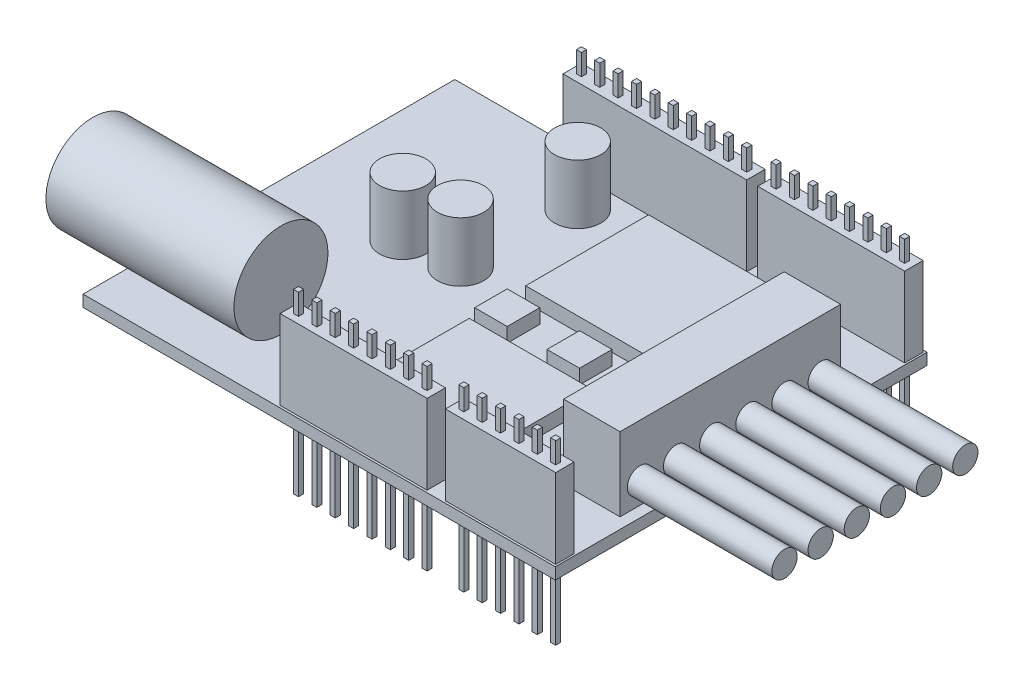
SolidWorks part; units mm, degrees
ref_plane "Plan de face" through (0, 0, 0) normal (0, 0, 1) x (1, 0, 0)
ref_plane "Plan de dessus" through (0, 0, 0) normal (0, 1, 0) x (1, 0, 0)
ref_plane "Plan de droite" through (0, 0, 0) normal (1, 0, 0) x (0, 0, -1)
sketch "Esquisse1" plane through (0, 0, 0) normal (0, 1, 0) x (1, 0, 0)
  line L1 (-32.65, 25.7) -> (32.65, 25.7)
  line L2 (-32.65, 25.7) -> (-32.65, -25.7)
  line L3 (-32.65, -25.7) -> (32.65, -25.7)
  line L4 (32.65, 25.7) -> (32.65, -25.7)
  point P4 (0, 25.7)
  point P6 (-32.65, 0)
  dimension "D1" = 65.3
  dimension "D2" = 51.4
extrude "Boss.-Extru.1" add sketch "Esquisse1" along normal blind 1.6
sketch "Esquisse2" plane through (0, 1.6, 0) normal (0, 1, 0) x (1, 0, 0)
  line L0 (0, 0) -> (8.1488, 0) construction
  line L1 (-1.05, 20.9) -> (15.95, 20.9)
  line L2 (-1.05, 20.9) -> (-1.05, 3.9)
  line L3 (-1.05, 3.9) -> (15.95, 3.9)
  line L4 (15.95, 20.9) -> (15.95, 3.9)
  line L5 (-1.05, -3.9) -> (15.95, -3.9)
  line L6 (15.95, -20.9) -> (15.95, -3.9)
  line L7 (-1.05, -20.9) -> (15.95, -20.9)
  line L8 (-1.05, -20.9) -> (-1.05, -3.9)
  line L9 (-32.65, 25.7) -> (-32.65, -25.7) construction
  line L10 (-1.95, 2.25) -> (2.55, 2.25)
  line L11 (-1.95, 2.25) -> (-1.95, -2.25)
  line L12 (-1.95, -2.25) -> (2.55, -2.25)
  line L13 (2.55, 2.25) -> (2.55, -2.25)
  line L14 (8.05, 2.25) -> (12.55, 2.25)
  line L15 (8.05, 2.25) -> (8.05, -2.25)
  line L16 (8.05, -2.25) -> (12.55, -2.25)
  line L17 (12.55, 2.25) -> (12.55, -2.25)
  point P15 (2.55, 0)
  dimension "D1" = 17
  dimension "D2" = 4.5
  dimension "D3" = 7.8
  dimension "D4" = 31.6
  dimension "D5" = 5.5
  dimension "D6" = 30.7
extrude "Boss.-Extru.2" add sketch "Esquisse2" along normal blind 2 separate body
sketch "Esquisse3" plane through (0, 1.6, 0) normal (0, 1, 0) x (1, 0, 0)
  line L0 (-32.65, 25.7) -> (-32.65, -25.7) construction
  line L1 (32.65, 25.7) -> (-32.65, 25.7) construction
  circle A0 centre (-8.55, 18.6) radius 3.2
  circle A1 centre (-9.75, 3.6) radius 3.2
  circle A2 centre (-16.95, 2.8) radius 3.2
  dimension "D1" = 6.4
  dimension "D2" = 15.7
  dimension "D3" = 22.9
  dimension "D4" = 24.1
  dimension "D5" = 7.1
  dimension "D6" = 22.1
  dimension "D7" = 22.9
extrude "Boss.-Extru.3" add sketch "Esquisse3" along normal blind 8.2 separate body
sketch "Esquisse4" plane through (0, 1.6, 0) normal (0, 1, 0) x (1, 0, 0)
  line L0 (32.65, -25.7) -> (32.65, 25.7) construction
  line L1 (23.35, 15.25) -> (31.15, 15.25)
  line L2 (23.35, 15.25) -> (23.35, -15.25)
  line L3 (23.35, -15.25) -> (31.15, -15.25)
  line L4 (31.15, 15.25) -> (31.15, -15.25)
  point P4 (23.35, 0)
  dimension "D1" = 7.8
  dimension "D2" = 30.5
  dimension "D3" = 1.5
extrude "Boss.-Extru.4" add sketch "Esquisse4" along normal blind 10.2 separate body
sketch "Esquisse5" plane through (31.15, 0, 0) normal (1, 0, 0) x (0, 0, -1)
  line L0 (0, 0) -> (0, 9.7249) construction
  line L1 (-15.25, 1.6) -> (15.25, 1.6) construction
  circle A0 centre (2.5, 4.6) radius 1.75
  circle A1 centre (-2.5, 4.6) radius 1.75
  circle A2 centre (7.5, 4.6) radius 1.75
  circle A3 centre (12.5, 4.6) radius 1.75
  circle A4 centre (-2.5, 4.6) radius 1.75
  circle A5 centre (2.5, 4.6) radius 1.75
  circle A6 centre (-12.5, 4.6) radius 1.75
  circle A7 centre (-7.5, 4.6) radius 1.75
  dimension "D2" = 3.5
  dimension "D1" = 3
  dimension "D3" = 5
  dimension "D4" = 2
  dimension "D5" = 2
extrude "Boss.-Extru.5" add sketch "Esquisse5" along normal blind 20 separate body contours A3 | A2 | A0 | A1 | A7 | A6
sketch "Esquisse6" plane through (-32.65, 0, 0) normal (-1, 0, 0) x (0, 0, 1)
  circle A0 centre (17.8373, 9.0901) radius 6.5
  dimension "D1" = 13
extrude "Boss.-Extru.6" add sketch "Esquisse6" against normal blind 19.5 and the other way blind 6.5 separate body
sketch "Esquisse7" plane through (0, 1.6, 0) normal (0, 1, 0) x (1, 0, 0)
  line L0 (0, 0) -> (32.4, 0) construction
  line L1 (12.08, 25.4) -> (32.4, 25.4)
  line L2 (12.08, 25.4) -> (12.08, 22.86)
  line L3 (12.08, 22.86) -> (32.4, 22.86)
  line L4 (32.4, 25.4) -> (32.4, 22.86)
  line L5 (32.4, -22.86) -> (32.4, 22.86) construction
  line L6 (10.56, 25.4) -> (-14.84, 25.4)
  line L7 (10.56, 25.4) -> (10.56, 22.86)
  line L8 (10.56, 22.86) -> (-14.84, 22.86)
  line L9 (-14.84, 25.4) -> (-14.84, 22.86)
  line L10 (17.16, -22.86) -> (32.4, -22.86)
  line L11 (17.16, -22.86) -> (17.16, -25.4)
  line L12 (17.16, -25.4) -> (32.4, -25.4)
  line L13 (32.4, -22.86) -> (32.4, -25.4)
  line L14 (-5.7, -22.86) -> (14.62, -22.86)
  line L15 (-5.7, -22.86) -> (-5.7, -25.4)
  line L16 (-5.7, -25.4) -> (14.62, -25.4)
  line L17 (14.62, -22.86) -> (14.62, -25.4)
  line L18 (32.65, -25.7) -> (32.65, 25.7) construction
  point P19 (32.4, -24.13)
  point P20 (32.4, 24.13)
  dimension "D1" = 2.54
  dimension "D2" = 20.32
  dimension "D3" = 25.4
  dimension "D4" = 1.52
  dimension "D5" = 15.24
  dimension "D6" = 20.32
  dimension "D7" = 2.54
  dimension "D8" = 48.26
  dimension "D9" = 0.25
extrude "Boss.-Extru.7" add sketch "Esquisse7" along normal blind 11 separate body
sketch "Esquisse8" plane through (0, 0, 0) normal (0, -1, 0) x (1, 0, 0)
  line L0 (12.08, -25.4) -> (12.08, -22.86) construction
  line L1 (13, -24.48) -> (13.7, -24.48)
  line L2 (13, -24.48) -> (13, -23.78)
  line L3 (13, -23.78) -> (13.7, -23.78)
  line L4 (13.7, -24.48) -> (13.7, -23.78)
  line L5 (16.24, -24.48) -> (16.24, -23.78)
  line L6 (15.54, -23.78) -> (16.24, -23.78)
  line L7 (15.54, -24.48) -> (15.54, -23.78)
  line L8 (15.54, -24.48) -> (16.24, -24.48)
  line L9 (18.78, -24.48) -> (18.78, -23.78)
  line L10 (18.08, -23.78) -> (18.78, -23.78)
  line L11 (18.08, -24.48) -> (18.08, -23.78)
  line L12 (18.08, -24.48) -> (18.78, -24.48)
  line L13 (21.32, -24.48) -> (21.32, -23.78)
  line L14 (20.62, -23.78) -> (21.32, -23.78)
  line L15 (20.62, -24.48) -> (20.62, -23.78)
  line L16 (20.62, -24.48) -> (21.32, -24.48)
  line L17 (23.86, -24.48) -> (23.86, -23.78)
  line L18 (23.16, -23.78) -> (23.86, -23.78)
  line L19 (23.16, -24.48) -> (23.16, -23.78)
  line L20 (23.16, -24.48) -> (23.86, -24.48)
  line L21 (26.4, -24.48) -> (26.4, -23.78)
  line L22 (25.7, -23.78) -> (26.4, -23.78)
  line L23 (25.7, -24.48) -> (25.7, -23.78)
  line L24 (25.7, -24.48) -> (26.4, -24.48)
  line L25 (28.94, -24.48) -> (28.94, -23.78)
  line L26 (28.24, -23.78) -> (28.94, -23.78)
  line L27 (28.24, -24.48) -> (28.24, -23.78)
  line L28 (28.24, -24.48) -> (28.94, -24.48)
  line L29 (31.48, -24.48) -> (31.48, -23.78)
  line L30 (30.78, -23.78) -> (31.48, -23.78)
  line L31 (30.78, -24.48) -> (30.78, -23.78)
  line L32 (30.78, -24.48) -> (31.48, -24.48)
  line L33 (10.56, -22.86) -> (10.56, -25.4) construction
  line L34 (9.64, -24.48) -> (8.94, -24.48)
  line L35 (9.64, -24.48) -> (9.64, -23.78)
  line L36 (9.64, -23.78) -> (8.94, -23.78)
  line L37 (8.94, -24.48) -> (8.94, -23.78)
  line L38 (7.1, -23.78) -> (6.4, -23.78)
  line L39 (6.4, -24.48) -> (6.4, -23.78)
  line L40 (7.1, -24.48) -> (6.4, -24.48)
  line L41 (7.1, -24.48) -> (7.1, -23.78)
  line L42 (4.56, -23.78) -> (3.86, -23.78)
  line L43 (3.86, -24.48) -> (3.86, -23.78)
  line L44 (4.56, -24.48) -> (3.86, -24.48)
  line L45 (4.56, -24.48) -> (4.56, -23.78)
  line L46 (2.02, -23.78) -> (1.32, -23.78)
  line L47 (1.32, -24.48) -> (1.32, -23.78)
  line L48 (2.02, -24.48) -> (1.32, -24.48)
  line L49 (2.02, -24.48) -> (2.02, -23.78)
  line L50 (-0.52, -23.78) -> (-1.22, -23.78)
  line L51 (-1.22, -24.48) -> (-1.22, -23.78)
  line L52 (-0.52, -24.48) -> (-1.22, -24.48)
  line L53 (-0.52, -24.48) -> (-0.52, -23.78)
  line L54 (-3.06, -23.78) -> (-3.76, -23.78)
  line L55 (-3.76, -24.48) -> (-3.76, -23.78)
  line L56 (-3.06, -24.48) -> (-3.76, -24.48)
  line L57 (-3.06, -24.48) -> (-3.06, -23.78)
  line L58 (-5.6, -23.78) -> (-6.3, -23.78)
  line L59 (-6.3, -24.48) -> (-6.3, -23.78)
  line L60 (-5.6, -24.48) -> (-6.3, -24.48)
  line L61 (-5.6, -24.48) -> (-5.6, -23.78)
  line L62 (-8.14, -23.78) -> (-8.84, -23.78)
  line L63 (-8.84, -24.48) -> (-8.84, -23.78)
  line L64 (-8.14, -24.48) -> (-8.84, -24.48)
  line L65 (-8.14, -24.48) -> (-8.14, -23.78)
  line L66 (-10.68, -23.78) -> (-11.38, -23.78)
  line L67 (-11.38, -24.48) -> (-11.38, -23.78)
  line L68 (-10.68, -24.48) -> (-11.38, -24.48)
  line L69 (-10.68, -24.48) -> (-10.68, -23.78)
  line L70 (-13.22, -23.78) -> (-13.92, -23.78)
  line L71 (-13.92, -24.48) -> (-13.92, -23.78)
  line L72 (-13.22, -24.48) -> (-13.92, -24.48)
  line L73 (-13.22, -24.48) -> (-13.22, -23.78)
  line L74 (14.62, 25.4) -> (14.62, 22.86) construction
  line L75 (18.08, 23.78) -> (18.78, 23.78)
  line L76 (18.08, 23.78) -> (18.08, 24.48)
  line L77 (18.08, 24.48) -> (18.78, 24.48)
  line L78 (18.78, 23.78) -> (18.78, 24.48)
  line L79 (13.7, 23.78) -> (13, 23.78)
  line L80 (13.7, 23.78) -> (13.7, 24.48)
  line L81 (13.7, 24.48) -> (13, 24.48)
  line L82 (13, 23.78) -> (13, 24.48)
  line L83 (17.16, 22.86) -> (17.16, 25.4) construction
  line L84 (21.32, 23.78) -> (21.32, 24.48)
  line L85 (20.62, 23.78) -> (21.32, 23.78)
  line L86 (20.62, 23.78) -> (20.62, 24.48)
  line L87 (20.62, 24.48) -> (21.32, 24.48)
  line L88 (23.86, 23.78) -> (23.86, 24.48)
  line L89 (23.16, 23.78) -> (23.86, 23.78)
  line L90 (23.16, 23.78) -> (23.16, 24.48)
  line L91 (23.16, 24.48) -> (23.86, 24.48)
  line L92 (26.4, 23.78) -> (26.4, 24.48)
  line L93 (25.7, 23.78) -> (26.4, 23.78)
  line L94 (25.7, 23.78) -> (25.7, 24.48)
  line L95 (25.7, 24.48) -> (26.4, 24.48)
  line L96 (28.94, 23.78) -> (28.94, 24.48)
  line L97 (28.24, 23.78) -> (28.94, 23.78)
  line L98 (28.24, 23.78) -> (28.24, 24.48)
  line L99 (28.24, 24.48) -> (28.94, 24.48)
  line L100 (31.48, 23.78) -> (31.48, 24.48)
  line L101 (30.78, 23.78) -> (31.48, 23.78)
  line L102 (30.78, 23.78) -> (30.78, 24.48)
  line L103 (30.78, 24.48) -> (31.48, 24.48)
  line L104 (11.16, 23.78) -> (10.46, 23.78)
  line L105 (11.16, 23.78) -> (11.16, 24.48)
  line L106 (11.16, 24.48) -> (10.46, 24.48)
  line L107 (10.46, 23.78) -> (10.46, 24.48)
  line L108 (8.62, 23.78) -> (7.92, 23.78)
  line L109 (8.62, 23.78) -> (8.62, 24.48)
  line L110 (8.62, 24.48) -> (7.92, 24.48)
  line L111 (7.92, 23.78) -> (7.92, 24.48)
  line L112 (6.08, 23.78) -> (5.38, 23.78)
  line L113 (6.08, 23.78) -> (6.08, 24.48)
  line L114 (6.08, 24.48) -> (5.38, 24.48)
  line L115 (5.38, 23.78) -> (5.38, 24.48)
  line L116 (3.54, 23.78) -> (2.84, 23.78)
  line L117 (3.54, 23.78) -> (3.54, 24.48)
  line L118 (3.54, 24.48) -> (2.84, 24.48)
  line L119 (2.84, 23.78) -> (2.84, 24.48)
  line L120 (1, 23.78) -> (0.3, 23.78)
  line L121 (1, 23.78) -> (1, 24.48)
  line L122 (1, 24.48) -> (0.3, 24.48)
  line L123 (0.3, 23.78) -> (0.3, 24.48)
  line L124 (-1.54, 23.78) -> (-2.24, 23.78)
  line L125 (-1.54, 23.78) -> (-1.54, 24.48)
  line L126 (-1.54, 24.48) -> (-2.24, 24.48)
  line L127 (-2.24, 23.78) -> (-2.24, 24.48)
  line L128 (-4.08, 23.78) -> (-4.78, 23.78)
  line L129 (-4.08, 23.78) -> (-4.08, 24.48)
  line L130 (-4.08, 24.48) -> (-4.78, 24.48)
  line L131 (-4.78, 23.78) -> (-4.78, 24.48)
  point P6 (12.08, -24.13)
  point P7 (13, -24.13)
  point P8 (13.35, -23.78)
  point P43 (10.56, -24.13)
  point P44 (9.64, -24.13)
  point P45 (9.29, -24.48)
  point P93 (14.62, 24.13)
  point P94 (13.7, 24.13)
  point P97 (17.16, 24.13)
  point P98 (18.08, 24.13)
  point P99 (13.35, 23.78)
  point P100 (18.43, 23.78)
  dimension "D1" = 0.7
  dimension "D2" = 1.27
  dimension "D4" = 1.27
  dimension "D6" = 1.27
  dimension "D7" = 1.27
  dimension "D3" = 8
  dimension "D5" = 10
  dimension "D8" = 6
  dimension "D9" = 8
extrude "Boss.-Extru.8" add sketch "Esquisse8" along normal blind 9 and the other way blind 15.5
equation "\"D4@Esquisse8\"=\"D2@Esquisse8\""
equation "\"D6@Esquisse8\"=\"D2@Esquisse8\""
equation "\"D7@Esquisse8\"=\"D2@Esquisse8\""
